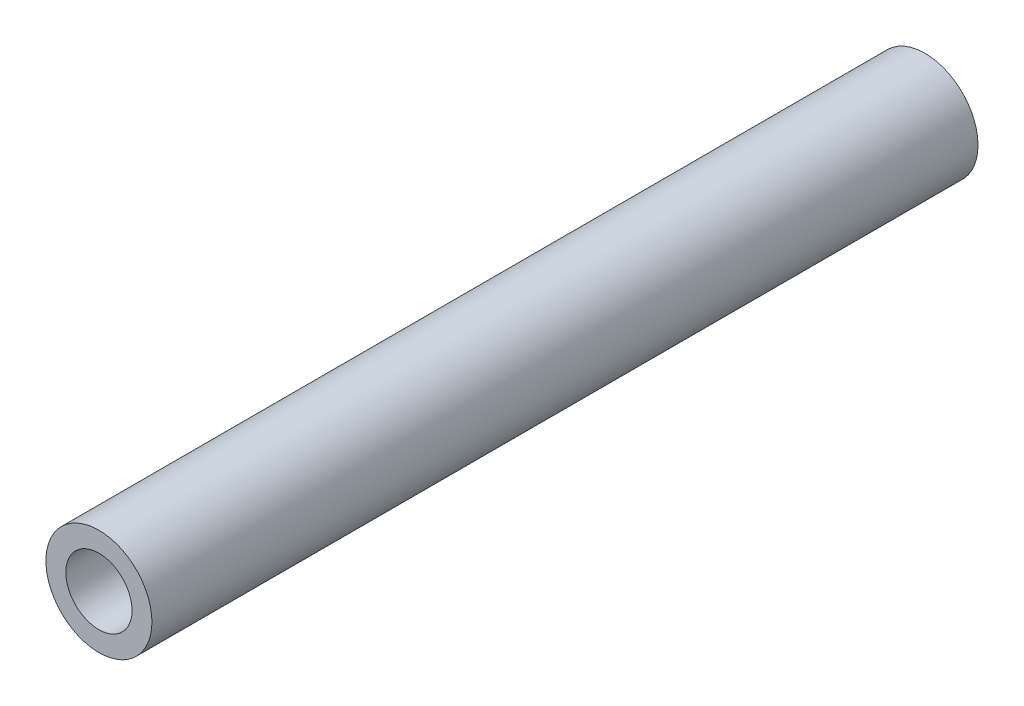
SolidWorks part; units mm, degrees
material "6063-T6, Rod (SS)"
ref_plane "Front Plane" through (0, 0, 0) normal (0, 0, 1) x (1, 0, 0)
ref_plane "Top Plane" through (0, 0, 0) normal (0, 1, 0) x (1, 0, 0)
ref_plane "Right Plane" through (0, 0, 0) normal (1, 0, 0) x (0, 0, -1)
sketch "Sketch1" plane through (0, 0, 0) normal (0, 0, 1) x (1, 0, 0)
  circle A0 centre (0, 0) radius 12
  circle A1 centre (0, 0) radius 7.5
  dimension "D1" = 15
  dimension "D2" = 24
extrude "Boss-Extrude1" add sketch "Sketch1" along normal blind 187
